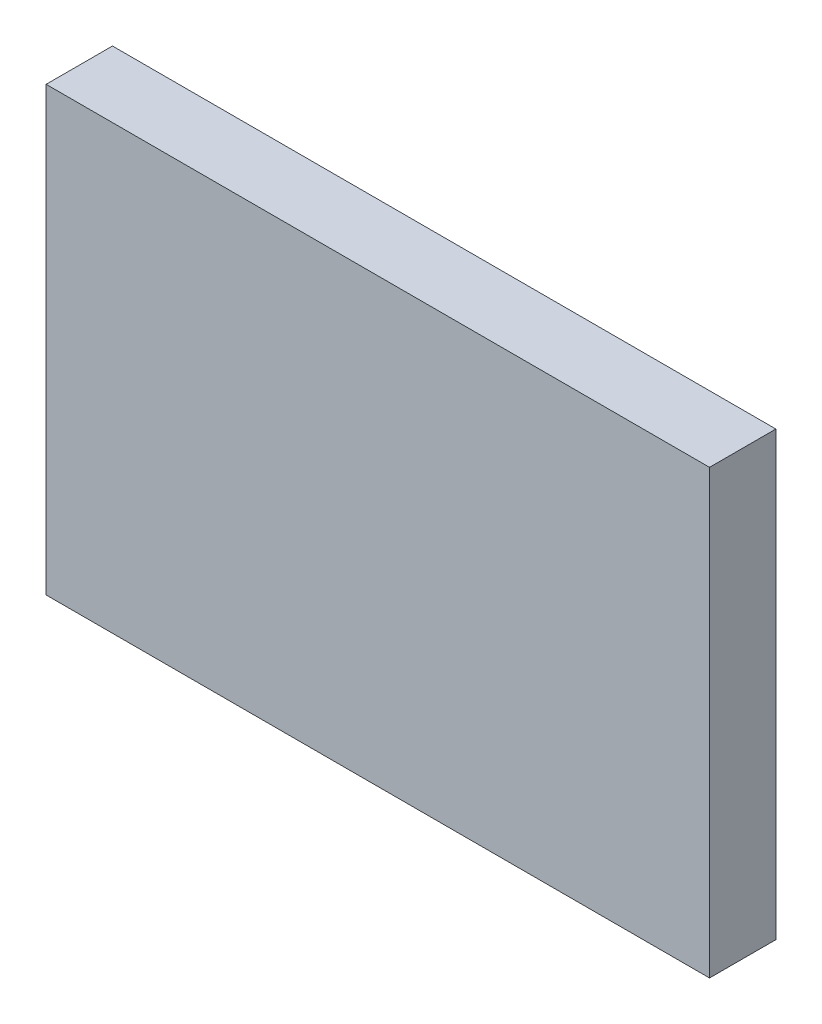
SolidWorks part; units mm, degrees
ref_plane "Ebene vorne" through (0, 0, 0) normal (0, 0, 1) x (1, 0, 0)
ref_plane "Ebene oben" through (0, 0, 0) normal (0, 1, 0) x (1, 0, 0)
ref_plane "Ebene rechts" through (0, 0, 0) normal (1, 0, 0) x (0, 0, -1)
sketch "Sketch1" plane through (0, 0, 0) normal (0, 0, 1) x (1, 0, 0)
  line L1 (0, 0) -> (30, 0)
  line L2 (0, 0) -> (0, 20)
  line L3 (0, 20) -> (30, 20)
  line L4 (30, 0) -> (30, 20)
  dimension "D1" = 30
  dimension "D2" = 20
extrude "Boss-Extrude1" add sketch "Sketch1" along normal blind 3
